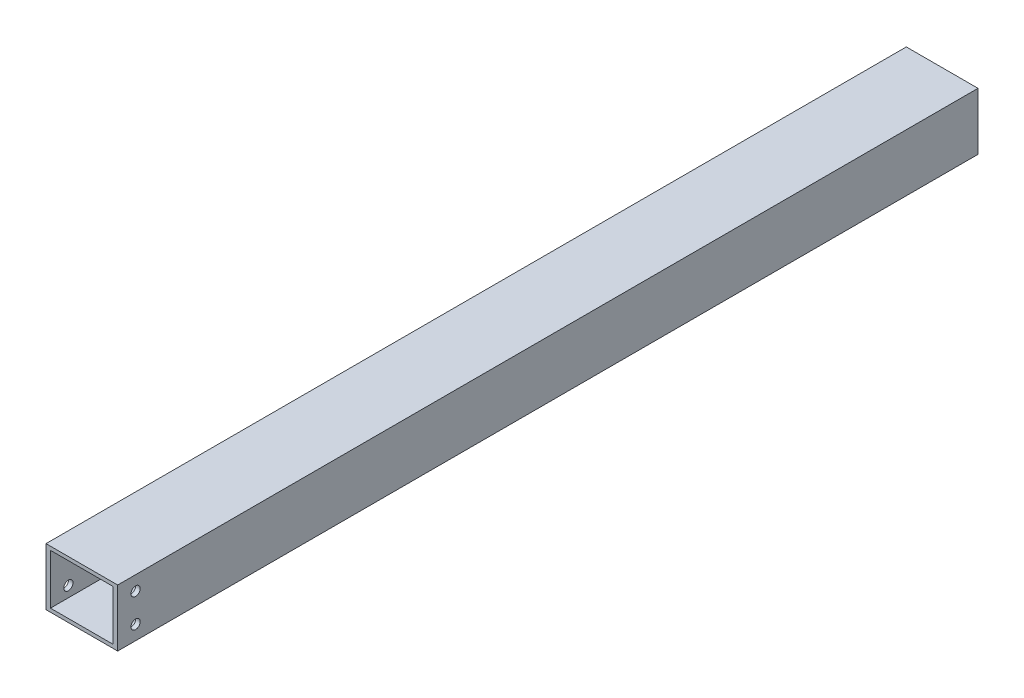
SolidWorks part; units mm, degrees
material "6063-T6"
ref_plane "Front Plane" through (0, 0, 0) normal (0, 0, 1) x (1, 0, 0)
ref_plane "Top Plane" through (0, 0, 0) normal (0, 1, 0) x (1, 0, 0)
ref_plane "Right Plane" through (0, 0, 0) normal (1, 0, 0) x (0, 0, -1)
sketch "Sketch1" plane through (0, 0, 0) normal (0, 0, 1) x (1, 0, 0)
  line L1 (-12.7, -10.1378) -> (12.7, -10.1378)
  line L2 (-12.7, -10.1378) -> (-12.7, 10.1378)
  line L3 (-12.7, 10.1378) -> (12.7, 10.1378)
  line L4 (12.7, -10.1378) -> (12.7, 10.1378)
  line L5 (-12.7, -10.1378) -> (12.7, 10.1378) construction
  line L6 (-12.7, 10.1378) -> (12.7, -10.1378) construction
  line L7 (-11.1125, -8.8706) -> (11.1125, -8.8706)
  line L8 (-11.1125, -8.8706) -> (-11.1125, 8.8706)
  line L9 (-11.1125, 8.8706) -> (11.1125, 8.8706)
  line L10 (11.1125, -8.8706) -> (11.1125, 8.8706)
  line L11 (-11.1125, -8.8706) -> (11.1125, 8.8706) construction
  line L12 (-11.1125, 8.8706) -> (11.1125, -8.8706) construction
  point P0 (0, 0)
  point P6 (0, 0)
  dimension "D1" = 25.4
  dimension "D2" = 22.225
extrude "Boss-Extrude2" add sketch "Sketch1" along normal blind 304.8
sketch "Sketch2" plane through (12.7, 0, 0) normal (1, 0, 0) x (0, 0, -1)
  line L0 (-304.8, 0) -> (-289.5916, 0) construction
  line L2 (-304.8, -10.1378) -> (-304.8, 10.1378) construction
  circle A0 centre (-298.45, -5.08) radius 1.632
  circle A1 centre (-298.45, 5.08) radius 1.632
  dimension "D1" = 3.2639
  dimension "D2" = 5.08
  dimension "D3" = 6.35
extrude "Cut-Extrude1" cut sketch "Sketch2" against normal through all
